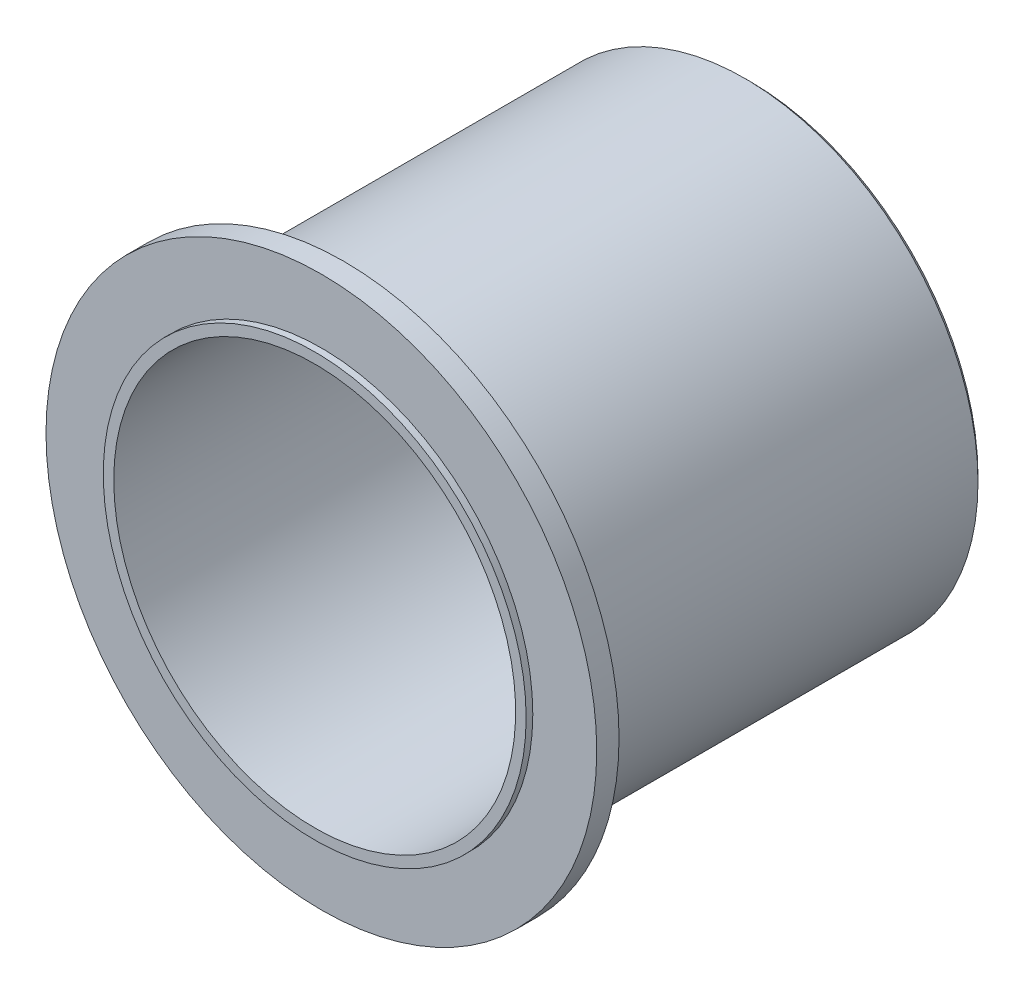
SolidWorks part; units mm, degrees
ref_plane "Front Plane" through (0, 0, 0) normal (0, 0, 1) x (1, 0, 0)
ref_plane "Top Plane" through (0, 0, 0) normal (0, 1, 0) x (1, 0, 0)
ref_plane "Right Plane" through (0, 0, 0) normal (1, 0, 0) x (0, 0, -1)
sketch "Sketch1" plane through (0, 0, 0) normal (0, 1, 0) x (1, 0, 0)
  line L0 (0, 0) -> (0, 65.35)
  line L1 (0, 65.35) -> (-35, 65.35)
  line L2 (-35, 65.35) -> (-35, 7.35)
  line L3 (-35, 7.35) -> (-41.35, 7.35)
  line L4 (-41.35, 7.35) -> (-41.35, 1)
  line L5 (-41.35, 1) -> (-31.75, 1)
  line L6 (-31.75, 1) -> (-31.75, 0)
  line L7 (-31.75, 0) -> (0, 0)
  dimension "D1" = 35
  dimension "D2" = 58
  dimension "D3" = 6.35
  dimension "D4" = 1
  dimension "D5" = 31.75
revolve "Revolve1" add sketch "Sketch1" angle 360 about L0
sketch "Sketch2" plane through (0, 0, -65.35) normal (0, 0, -1) x (-1, 0, 0)
  circle A0 centre (0, 0) radius 30.175
  dimension "D1" = 60.35
extrude "Cut-Extrude1" cut sketch "Sketch2" against normal through all
chamfer "Chamfer1" distance 0.75 angle 45 2 edges at (35, 0, -7.35) (35, 0, -65.35)
chamfer "Chamfer2" distance 3 angle 60 1 edges at (41.35, 0, -7.35)
fillet "Fillet1" radius 3 1 edges at (-30.175, 0, -65.35)
